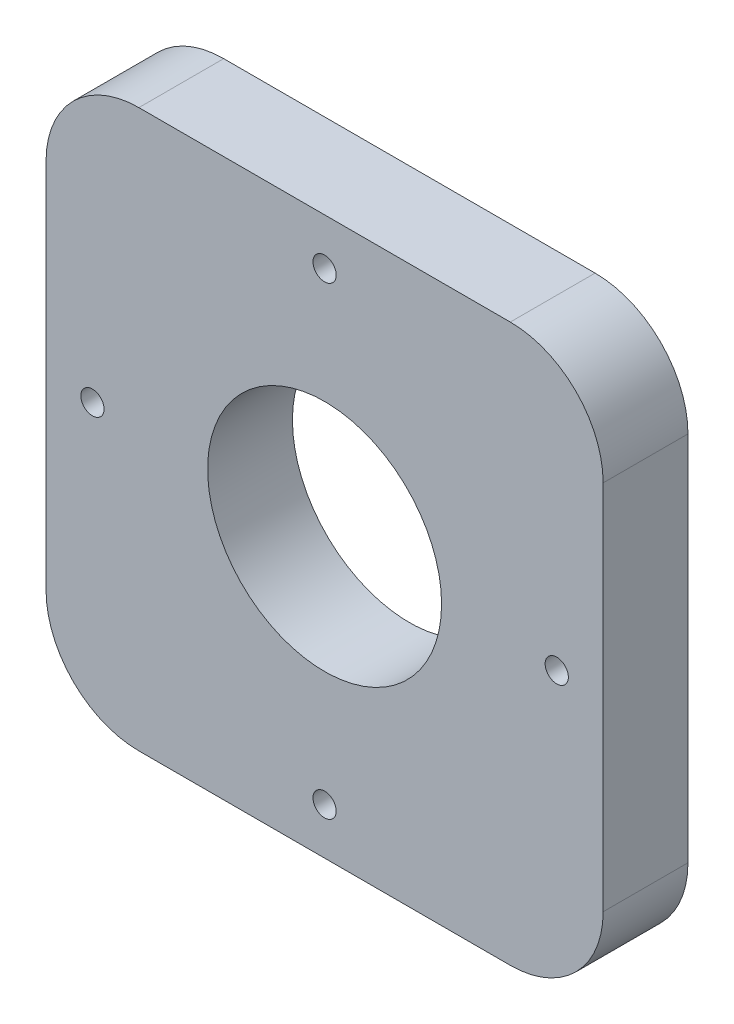
SolidWorks part; units mm, degrees
material "Acrylic (Medium-high impact)"
ref_plane "Front Plane" through (0, 0, 0) normal (0, 0, 1) x (1, 0, 0)
ref_plane "Top Plane" through (0, 0, 0) normal (0, 1, 0) x (1, 0, 0)
ref_plane "Right Plane" through (0, 0, 0) normal (1, 0, 0) x (0, 0, -1)
sketch "Sketch1" plane through (0, 0, 0) normal (0, 0, 1) x (1, 0, 0)
  line L0 (0, 0) -> (0, 19.05) construction
  line L1 (19.05, 19.05) -> (-19.05, 19.05)
  line L2 (0, 0) -> (-19.05, 19.05) construction
  line L3 (-19.05, 19.05) -> (-19.05, -19.05)
  line L4 (-19.05, 0) -> (0, 0) construction
  line L7 (19.05, 19.05) -> (19.05, -19.05)
  line L8 (19.05, -19.05) -> (-19.05, -19.05)
  point P18 (19.05, 0)
  dimension "D2" = 19.05
extrude "Boss-Extrude1" add sketch "Sketch1" along normal blind 5.8
sketch "Sketch2" plane through (0, 0, 5.8) normal (0, 0, 1) x (1, 0, 0)
  line L0 (19.05, 0) -> (-19.05, 0) construction
  line L1 (19.05, -19.05) -> (19.05, 19.05) construction
  line L2 (-19.05, 19.05) -> (-19.05, -19.05) construction
  line L3 (0, 0) -> (0, 15.875) construction
  line L5 (19.05, 19.05) -> (-19.05, 19.05) construction
  circle A0 centre (0, 15.875) radius 0.7937
  circle A1 centre (15.875, 0) radius 0.7937
  circle A2 centre (0, -15.875) radius 0.7938
  circle A3 centre (-15.875, 0) radius 0.7937
  dimension "D1" = 1.5875
  dimension "D2" = 3.175
  dimension "D3" = 4
extrude "Cut-Extrude1" cut sketch "Sketch2" against normal through all
sketch "Sketch3" plane through (0, 0, 5.8) normal (0, 0, 1) x (1, 0, 0)
  circle A0 centre (0, 0) radius 8
  dimension "D1" = 16
extrude "Cut-Extrude2" cut sketch "Sketch3" against normal blind 12.7
fillet "Fillet1" radius 6.35 4 edges at (19.05, 19.05, 2.9) (-19.05, 19.05, 2.9) (-19.05, -19.05, 2.9) (19.05, -19.05, 2.9)
other "Move Face1" [suppressed] parameters "D1"=0.2
